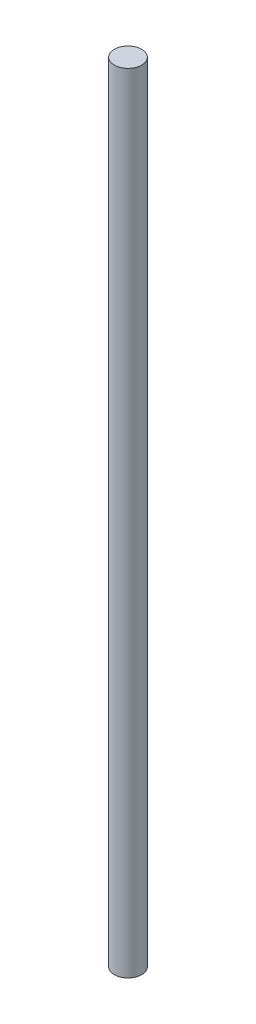
SolidWorks part; units mm, degrees
material "AISI 1020"
ref_plane "Front Plane" through (0, 0, 0) normal (0, 0, 1) x (1, 0, 0)
ref_plane "Top Plane" through (0, 0, 0) normal (0, 1, 0) x (1, 0, 0)
ref_plane "Right Plane" through (0, 0, 0) normal (1, 0, 0) x (0, 0, -1)
sketch "Sketch1" plane through (0, 0, 0) normal (0, 1, 0) x (1, 0, 0)
  circle A0 centre (0, 0) radius 4
  dimension "D1" = 8
extrude "Boss-Extrude1" add sketch "Sketch1" along normal blind 230
